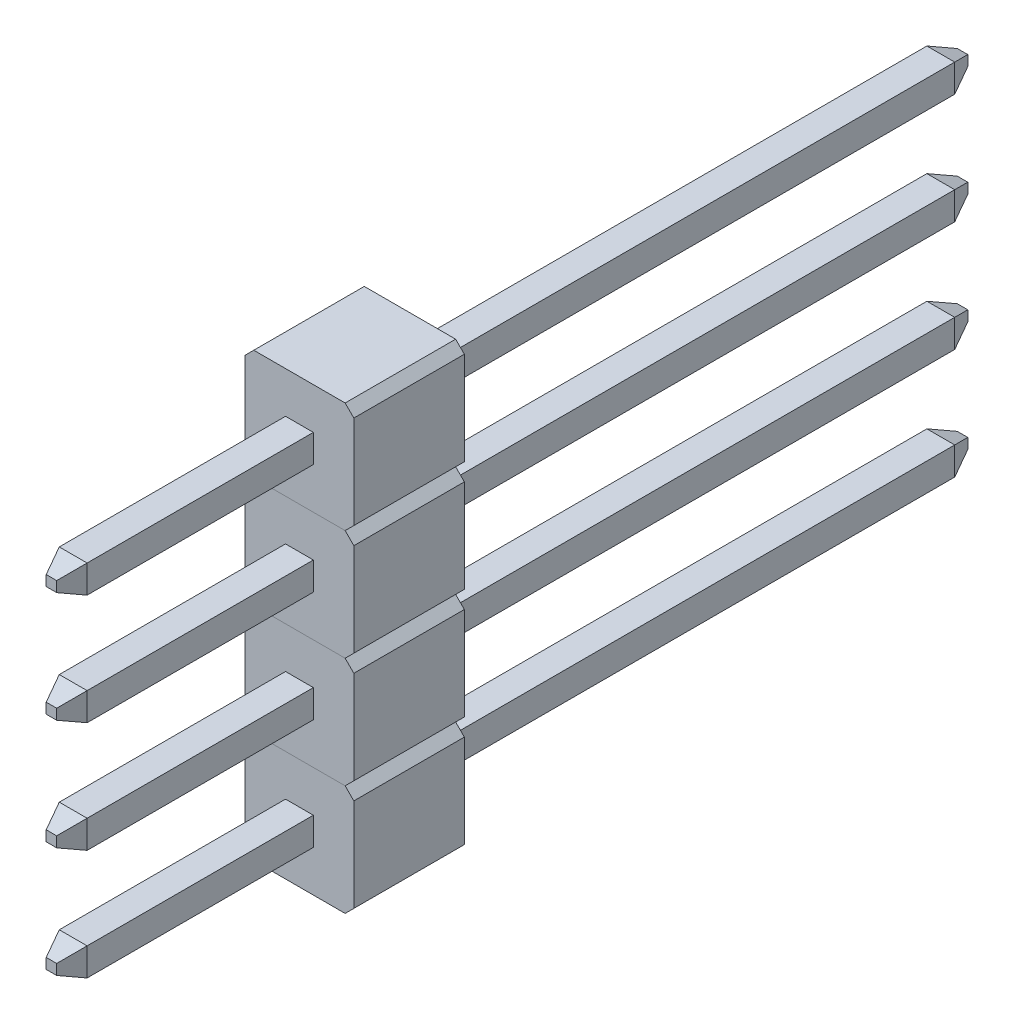
SolidWorks part; units mm, degrees
ref_plane "Plan de face" through (0, 0, 0) normal (0, 0, 1) x (1, 0, 0)
ref_plane "Plan de dessus" through (0, 0, 0) normal (0, 1, 0) x (1, 0, 0)
ref_plane "Plan de droite" through (0, 0, 0) normal (1, 0, 0) x (0, 0, -1)
sketch "Esquisse1" plane through (0, 0, 0) normal (0, 0, 1) x (1, 0, 0)
  line L1 (-1.25, 1.27) -> (1.25, 1.27)
  line L2 (-1.25, 1.27) -> (-1.25, -1.27)
  line L3 (-1.25, -1.27) -> (1.25, -1.27)
  line L4 (1.25, 1.27) -> (1.25, -1.27)
  line L5 (-1.25, 1.27) -> (1.25, -1.27) construction
  line L6 (-1.25, -1.27) -> (1.25, 1.27) construction
  point P0 (0, 0)
  dimension "D1" = 2.5
  dimension "D2" = 2.54
extrude "Base" add sketch "Esquisse1" along normal blind 2.54
sketch "Esquisse3" plane through (0, 0, 2.54) normal (0, 0, 1) x (1, 0, 0)
  line L1 (-0.32, -0.32) -> (0.32, -0.32)
  line L2 (-0.32, -0.32) -> (-0.32, 0.32)
  line L3 (-0.32, 0.32) -> (0.32, 0.32)
  line L4 (0.32, -0.32) -> (0.32, 0.32)
  line L5 (-0.32, -0.32) -> (0.32, 0.32) construction
  line L6 (-0.32, 0.32) -> (0.32, -0.32) construction
  point P0 (0, 0)
  dimension "D1" = 0.64
extrude "A" add sketch "Esquisse3" along normal blind 5.7
sketch "Esquisse4" plane through (0, 0, 0) normal (0, 0, -1) x (-1, 0, 0)
  line L1 (-0.32, 0.32) -> (0.32, 0.32)
  line L2 (-0.32, 0.32) -> (-0.32, -0.32)
  line L3 (-0.32, -0.32) -> (0.32, -0.32)
  line L4 (0.32, 0.32) -> (0.32, -0.32)
  line L5 (-0.32, 0.32) -> (0.32, -0.32) construction
  line L6 (-0.32, -0.32) -> (0.32, 0.32) construction
  point P0 (0, 0)
  dimension "D1" = 0.64
extrude "B" add sketch "Esquisse4" along normal blind 12.7
chamfer "Chanfrein2" distance 0.2 angle 45 4 edges at (1.25, -1.27, 1.27) (1.25, 1.27, 1.27) (-1.25, 1.27, 1.27) (-1.25, -1.27, 1.27)
chamfer "Chanfrein3" distance 0.5 distance2 0.2 8 edges at (0, -0.32, 8.24) (-0.32, 0, 8.24) (0, 0.32, 8.24) (0.32, 0, 8.24) (0, -0.32, -12.7) (0.32, 0, -12.7) (0, 0.32, -12.7) (-0.32, 0, -12.7)
pattern_linear "Répétition linéaire2" count 4 spacing 2.54 along (0, 1, 0) of bodies 103
